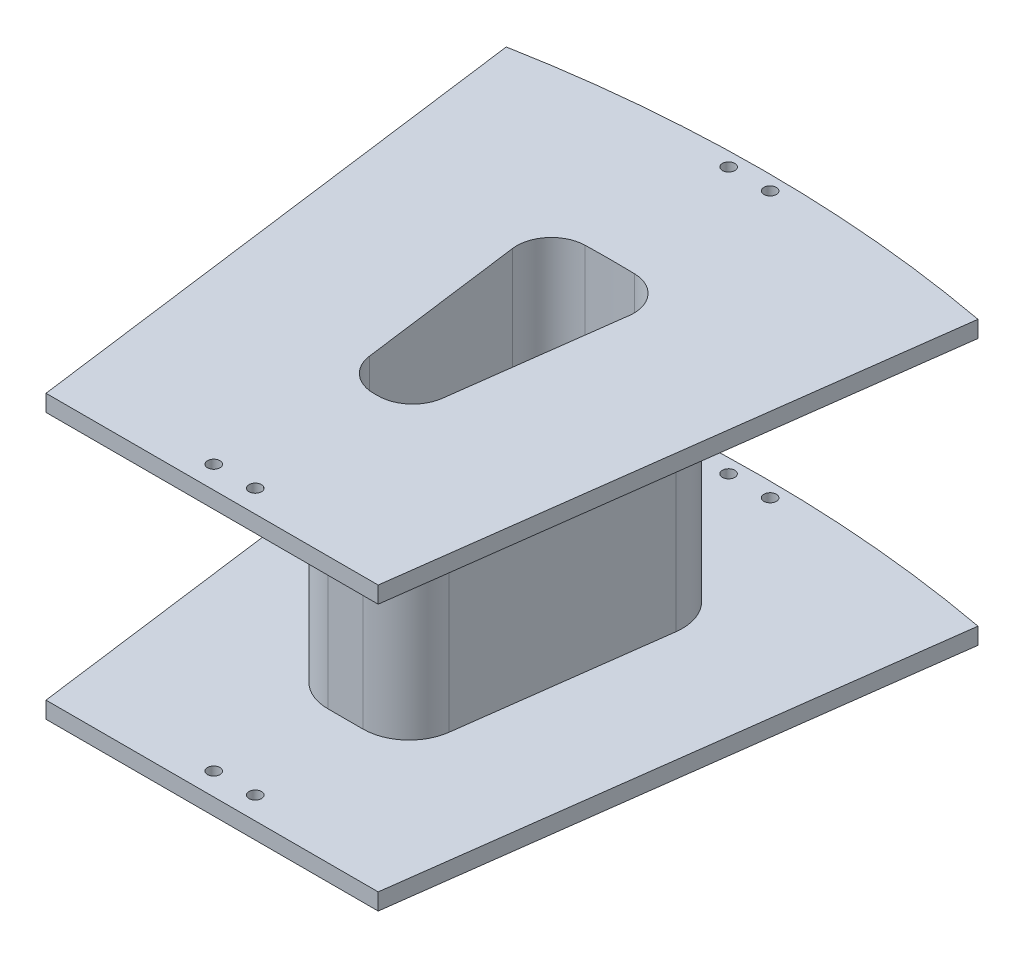
SolidWorks part; units mm, degrees
material "ABS"
ref_plane "Front Plane" through (0, 0, 0) normal (0, 0, 1) x (1, 0, 0)
ref_plane "Top Plane" through (0, 0, 0) normal (0, 1, 0) x (1, 0, 0)
ref_plane "Right Plane" through (0, 0, 0) normal (1, 0, 0) x (0, 0, -1)
sketch "Sketch1" plane through (0, 0, 0) normal (0, 1, 0) x (1, 0, 0)
  line L2 (-56.8062, 60.2594) -> (-40, -67.3966)
  line L3 (56.8062, 60.2594) -> (40, -67.3966)
  line L4 (0, 108.1999) -> (0, -114.8862) construction
  line L5 (-39.4678, 0) -> (38.1525, 0) construction
  line L6 (-9.0806, 62) -> (9.4787, 62) construction
  line L7 (-7.6404, -62) -> (7.7511, -62) construction
  line L8 (-40, -67.3966) -> (40, -67.3966)
  arc A2 (-56.8062, 60.2594) -> (56.8062, 60.2594) centre (0, -245) cw
  arc A3 (40, -67.3966) -> (-40, -67.3966) centre (0, -400) ccw construction
  circle A4 centre (-5, 62) radius 1.5
  circle A5 centre (-5, -62) radius 1.5
  circle A6 centre (5, -62) radius 1.5
  circle A7 centre (5, 62) radius 1.5
  point P24 (0, 65.5)
  point P25 (0, -65)
  dimension "D4" = 3
  dimension "D8" = 3
  dimension "D1" = 7.5
  dimension "D2" = 62
  dimension "D3" = 245
  dimension "D5" = 5
  dimension "D6" = 3
  dimension "D7" = 3.5
  dimension "D9" = 400
  dimension "D10" = 40
extrude "Boss-Extrude1" add sketch "Sketch1" along normal blind 4
sketch "Sketch2" plane through (0, 4, 0) normal (0, 1, 0) x (1, 0, 0)
  line L2 (-23.1616, 34.5421) -> (-13.971, -35.2675)
  line L8 (13.971, -35.2675) -> (23.1616, 34.5421)
  line L10 (-56.8062, 60.2594) -> (-40, -67.3966)
  line L11 (40, -67.3966) -> (56.8062, 60.2594)
  line L14 (-56.8062, 60.2594) -> (-40, -67.3966) construction
  line L15 (40, -67.3966) -> (56.8062, 60.2594) construction
  line L16 (-13.971, -35.2675) -> (13.971, -35.2675)
  line L19 (-40, -67.3966) -> (40, -67.3966)
  line L20 (-40, -67.3966) -> (40, -67.3966)
  arc A2 (23.1616, 34.5421) -> (-23.1616, 34.5421) centre (0, -245) ccw
  arc A8 (13.971, -35.2675) -> (-13.971, -35.2675) centre (0, -400) ccw construction
  arc A10 (56.8062, 60.2594) -> (-56.8062, 60.2594) centre (0, -245) ccw
  arc A22 (56.8062, 60.2594) -> (-56.8062, 60.2594) centre (0, -245) ccw construction
  arc A28 (40, -67.3966) -> (-40, -67.3966) centre (0, -400) ccw construction
  dimension "D1" = 0
  dimension "D2" = 30
extrude "Boss-Extrude2" add sketch "Sketch2" along normal blind 60 contours L8 A2 L2 L16
ref_plane "Plane1" through (0, 34, 0) normal (0, 1, 0) x (1, 0, 0)
mirror "Mirror1" about plane through (0, 34, 0) normal (0, 1, 0) of "Boss-Extrude1"
scale "Scale1" scale about centroid uniform scaling yes scale factor 0.27
fillet "Fillet1" radius 3 4 edges at (-6.2536, 34, -11.1975) (6.2536, 34, -11.1975) (3.7722, 34, 7.651) (-3.7722, 34, 7.651)
sketch "Sketch3" plane through (0, 43.18, 0) normal (0, 1, 0) x (1, 0, 0)
  line L0 (-3.7841, 6.9956) -> (-2.3731, -3.7213)
  line L1 (2.3731, -3.7213) -> (3.7841, 6.9956)
  line L2 (-15.3377, 18.1412) -> (-10.8, -16.3259)
  line L3 (10.8, -16.3259) -> (15.3377, 18.1412)
  line L4 (-15.3377, 18.1412) -> (-10.8, -16.3259) construction
  line L5 (10.8, -16.3259) -> (15.3377, 18.1412) construction
  line L6 (-4.1061, 9.4419) -> (-2.1127, -5.6998) construction
  line L7 (2.1127, -5.6998) -> (4.1061, 9.4419) construction
  line L11 (-10.8, -16.3259) -> (10.8, -16.3259)
  line L12 (-10.8, -16.3259) -> (10.8, -16.3259)
  arc A0 (1.6021, 9.5388) -> (-1.6021, 9.5388) centre (0, -64.2788) ccw
  arc A1 (0.1393, -5.6776) -> (-0.1393, -5.6776) centre (0, -105.9447) ccw
  arc A2 (15.3377, 18.1412) -> (-15.3377, 18.1412) centre (0, -64.2788) ccw
  arc A4 (15.3377, 18.1412) -> (-15.3377, 18.1412) centre (0, -64.2788) ccw construction
  arc A6 (4.1061, 9.4419) -> (-4.1061, 9.4419) centre (0, -64.2788) ccw construction
  arc A7 (-3.7841, 6.9956) -> (-1.6021, 9.5388) centre (-1.5533, 7.2893) cw
  arc A8 (1.6021, 9.5388) -> (3.7841, 6.9956) centre (1.5533, 7.2893) cw
  arc A9 (2.1127, -5.6998) -> (-2.1127, -5.6998) centre (0, -105.9447) ccw construction
  arc A10 (-2.3731, -3.7213) -> (-0.1393, -5.6776) centre (-0.1424, -3.4276) ccw
  arc A11 (2.3731, -3.7213) -> (0.1393, -5.6776) centre (0.1424, -3.4276) cw
  arc A14 (10.8, -16.3259) -> (-10.8, -16.3259) centre (0, -105.9447) ccw construction
  dimension "D3" = 2.25
  dimension "D4" = 2.25
  dimension "D1" = 0
  dimension "D2" = 10
extrude "Cut-Extrude1" cut sketch "Sketch3" against normal blind 20 contours A11 L1 A8 A0 A7 L0 A10 A1
